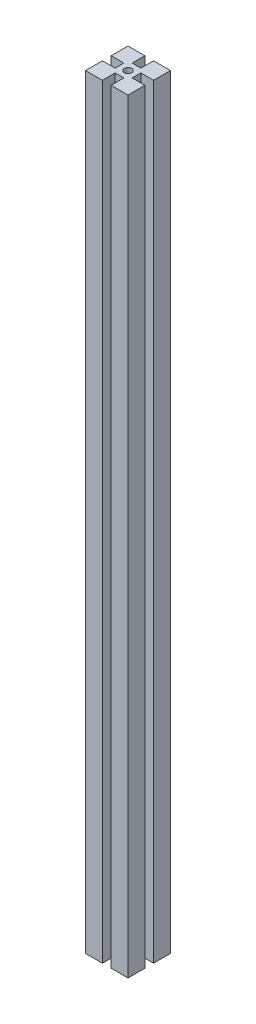
SolidWorks part; units mm, degrees
ref_plane "Ebene vorne" through (0, 0, 0) normal (0, 0, 1) x (1, 0, 0)
ref_plane "Ebene oben" through (0, 0, 0) normal (0, 1, 0) x (1, 0, 0)
ref_plane "Ebene rechts" through (0, 0, 0) normal (1, 0, 0) x (0, 0, -1)
sketch "Skizze1" plane through (0, 0, 0) normal (0, 1, 0) x (1, 0, 0)
  line L0 (-4.1, -20) -> (-4.1, -8)
  line L1 (-20, 20) -> (-4.1, 20)
  line L2 (-20, 20) -> (-20, 4.1)
  line L3 (-20, -20) -> (-4.1, -20)
  line L4 (20, 20) -> (20, 4.1)
  line L5 (-20, 20) -> (20, -20) construction
  line L6 (-20, -20) -> (20, 20) construction
  line L7 (-4.1, -8) -> (4.1, -8)
  line L8 (4.1, -8) -> (4.1, -20)
  line L9 (0, 53.9798) -> (0, -29.8049) construction
  line L10 (4.1, -20) -> (20, -20)
  line L11 (-42.3353, 0) -> (35.9872, 0) construction
  line L12 (4.1, 8) -> (4.1, 20)
  line L13 (-4.1, 20) -> (-4.1, 8)
  line L14 (-4.1, 8) -> (4.1, 8)
  line L15 (4.1, 20) -> (20, 20)
  line L16 (-20, 4.1) -> (-8, 4.1)
  line L17 (-8, 4.1) -> (-8, -4.1)
  line L18 (-8, -4.1) -> (-20, -4.1)
  line L19 (-20, -4.1) -> (-20, -20)
  line L20 (8, 4.1) -> (8, -4.1)
  line L21 (8, -4.1) -> (20, -4.1)
  line L22 (20, 4.1) -> (8, 4.1)
  line L23 (20, -4.1) -> (20, -20)
  circle A0 centre (0, 0) radius 3.5
  point P0 (0, 0)
  dimension "D7" = 7
  dimension "D1" = 40
  dimension "D2" = 8.2
  dimension "D3" = 12
  dimension "D4" = 40
  dimension "D5" = 8.2
  dimension "D6" = 12
extrude "Aufsatz-Linear austragen1" add sketch "Skizze1" along normal blind 720
